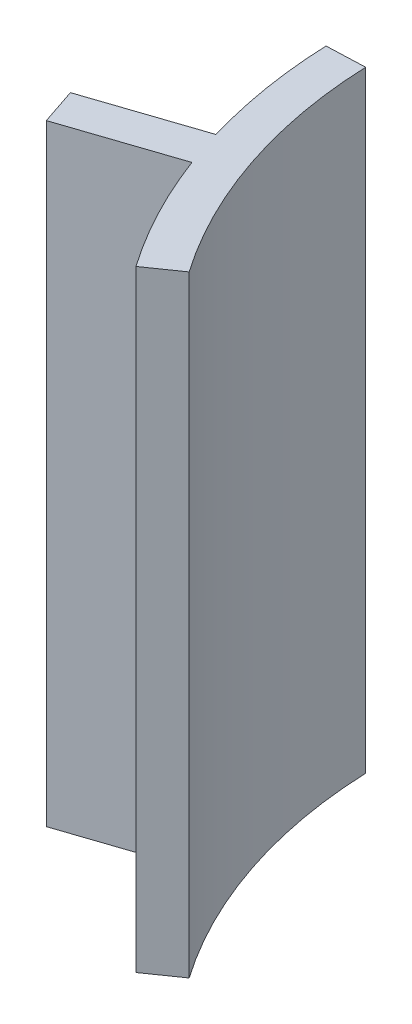
SolidWorks part; units mm, degrees
ref_plane "Front Plane" through (0, 0, 0) normal (0, 0, 1) x (1, 0, 0)
ref_plane "Top Plane" through (0, 0, 0) normal (0, 1, 0) x (1, 0, 0)
ref_plane "Right Plane" through (0, 0, 0) normal (1, 0, 0) x (0, 0, -1)
sketch "Sketch1" plane through (0, 0, 0) normal (0, 1, 0) x (1, 0, 0)
  line L0 (-64.9537, -2.4533) -> (-69.9501, -2.642) construction
  line L1 (-64.9537, -2.4533) -> (-69.9501, -2.642)
  line L2 (-57.4085, -40.0532) -> (-53.3079, -37.1923)
  line L4 (-79.7973, -29.3877) -> (-81.3866, -24.647)
  line L5 (-81.3866, -24.647) -> (-67.1221, -19.865)
  line L6 (-79.7973, -29.3877) -> (-65.5329, -24.6057)
  arc A0 (-64.9537, -2.4533) -> (-53.3079, -37.1923) centre (0, 0) ccw
  arc A1 (-69.9501, -2.642) -> (-67.1221, -19.865) centre (0, 0) ccw
  arc A2 (-67.1221, -19.865) -> (-69.9501, -2.642) centre (0, 0) cw
  arc A3 (-67.1221, -19.865) -> (-69.9501, -2.642) centre (0, 0) cw
  arc A4 (-65.5329, -24.6057) -> (-57.4085, -40.0532) centre (0, 0) ccw
  arc A5 (-57.4085, -40.0532) -> (-65.5329, -24.6057) centre (0, 0) cw
  arc A6 (-57.4085, -40.0532) -> (-65.5329, -24.6057) centre (0, 0) cw
  point P4 (0, 0)
  point P13 (-80.592, -27.0173)
extrude "Boss-Extrude1" add sketch "Sketch1" along normal blind 80 contours L6 A4 L2 A0 L1 A1 L5 L4
